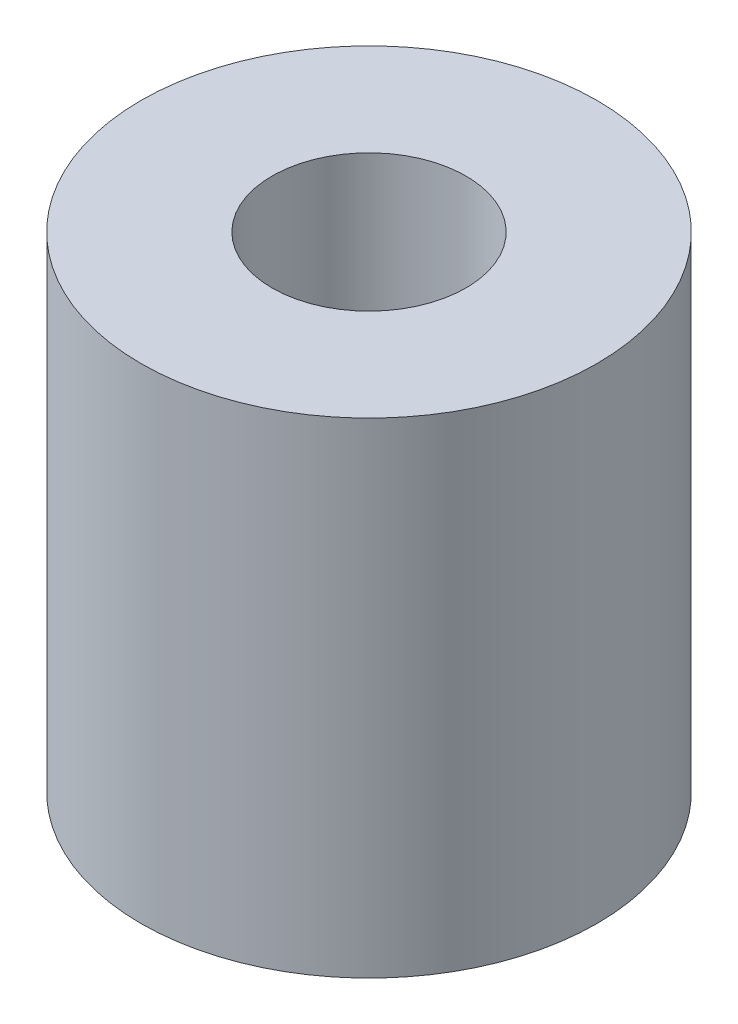
SolidWorks part; units mm, degrees
ref_plane "Alzado" through (0, 0, 0) normal (0, 0, 1) x (1, 0, 0)
ref_plane "Planta" through (0, 0, 0) normal (0, 1, 0) x (1, 0, 0)
ref_plane "Vista lateral" through (0, 0, 0) normal (1, 0, 0) x (0, 0, -1)
sketch "Croquis1" plane through (0, 0, 0) normal (0, 1, 0) x (1, 0, 0)
  circle A0 centre (0, 0) radius 11.75
  circle A1 centre (0, 0) radius 5
  dimension "D1" = 23.5
  dimension "D2" = 10
extrude "Saliente-Extruir1" add sketch "Croquis1" along normal blind 25
